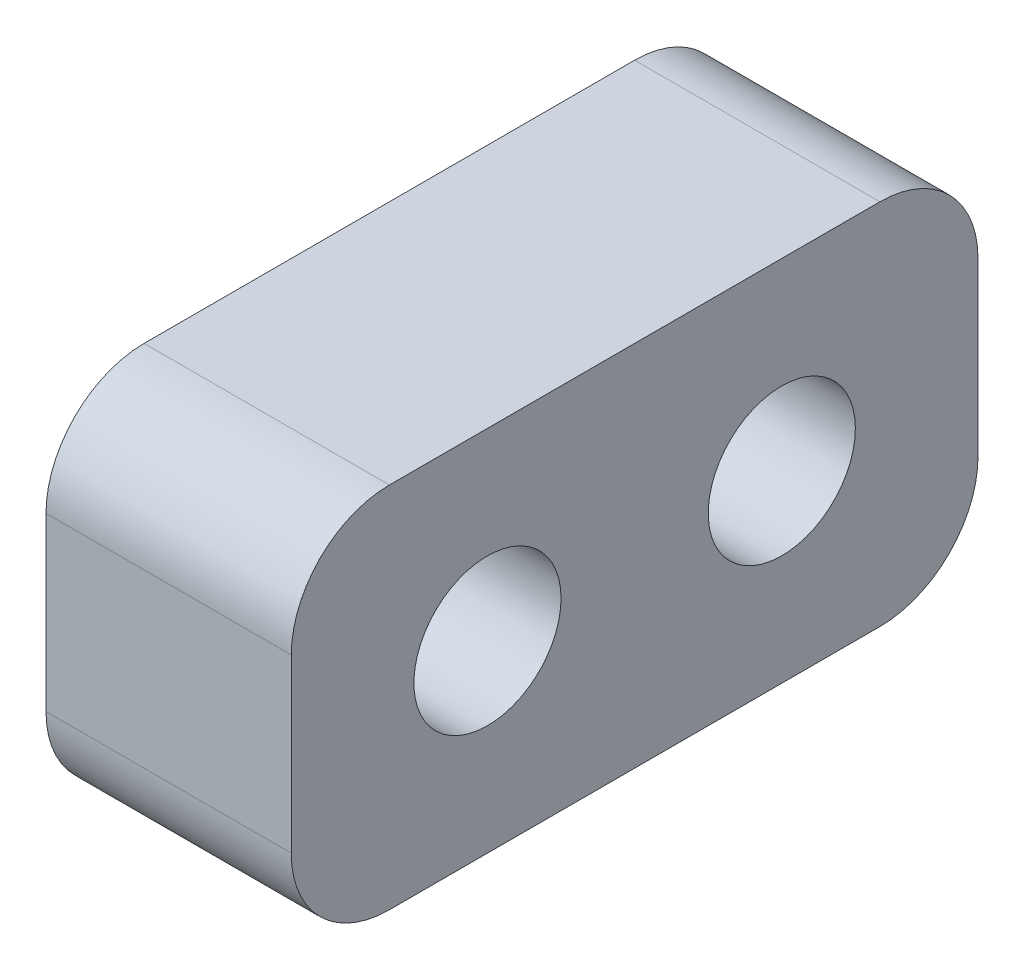
SolidWorks part; units mm, degrees
ref_plane "Front Plane" through (0, 0, 0) normal (1, 0, 0) x (0, 1, 0)
ref_plane "Top Plane" through (0, 0, 0) normal (0, 0, 1) x (0, 1, 0)
ref_plane "Right Plane" through (0, 0, 0) normal (0, 1, 0) x (-1, 0, 0)
sketch "Sketch1" plane through (0, 0, 0) normal (1, 0, 0) x (0, 1, 0)
  line L0 (0, 2) -> (0, 12)
  line L1 (2, 14) -> (5.5, 14)
  line L5 (5.5, 0) -> (2, 0)
  line L7 (7.5, 12) -> (7.5, 2)
  line L8 (0, 7) -> (13.3086, 7) construction
  arc A0 (7.5, 2) -> (5.5, 0) centre (5.5, 2) cw
  arc A1 (0, 2) -> (2, 0) centre (2, 2) ccw
  arc A2 (0, 12) -> (2, 14) centre (2, 12) cw
  arc A6 (7.5, 12) -> (5.5, 14) centre (5.5, 12) ccw
  circle A7 centre (3.75, 10) radius 1.5
  circle A8 centre (3.75, 4) radius 1.5
  point P12 (0, 0)
  point P18 (0, 0)
  point P19 (3.75, 14)
  dimension "D3" = 2
  dimension "D2" = 2
  dimension "D4" = 3
  dimension "D1" = 7.5
  dimension "D5" = 10
  dimension "D6" = 3
extrude "Boss-Extrude1" add sketch "Sketch1" along normal blind 5
